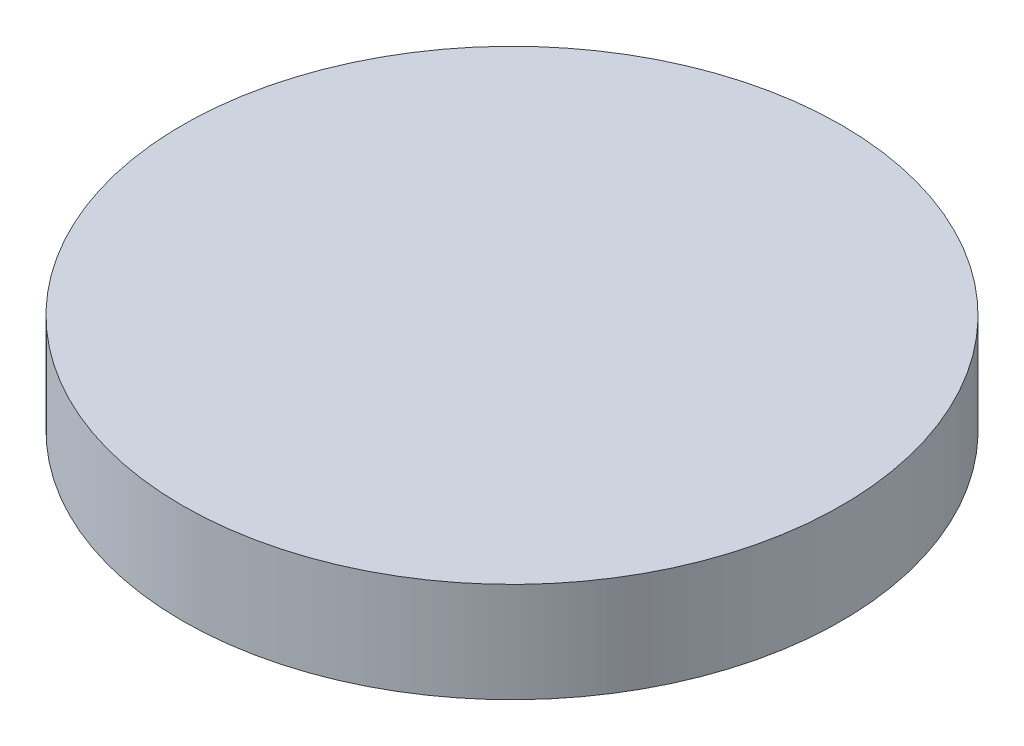
SolidWorks part; units mm, degrees
ref_plane "Front" through (0, 0, 0) normal (0, 0, 1) x (1, 0, 0)
ref_plane "Top" through (0, 0, 0) normal (0, 1, 0) x (1, 0, 0)
ref_plane "Right" through (0, 0, 0) normal (1, 0, 0) x (0, 0, -1)
sketch "Base Sketch" plane through (0, 0, 0) normal (0, 1, 0) x (1, 0, 0)
  circle A0 centre (0, 0) radius 1.65
  dimension "D1" = 3.3
extrude "Base" add sketch "Base Sketch" along normal blind 0.5
sketch "Base Slot Sketch" [suppressed] plane through (0, 1, 0) normal (0, 1, 0) x (-1, 0, 0)
  line L0 (-1.6008, -0.4) -> (1.6008, -0.4)
  line L1 (1.6008, 0.4) -> (-1.6008, 0.4)
  line L2 (0, 0) -> (-1.098, 0) construction
  circle A0 centre (0, 0) radius 1.65 construction
  arc A1 (1.6008, -0.4) -> (1.6008, 0.4) centre (0, 0) ccw
  arc A2 (-1.6008, 0.4) -> (-1.6008, -0.4) centre (0, 0) ccw
  dimension "D1" = 0.8
extrude "Base Slot" [suppressed] cut sketch "Base Slot Sketch" against normal blind 0.2
sketch "PLLT Extrusion Sketch" [suppressed] plane through (0, 2.5, 0) normal (0, 1, 0) x (-1, 0, 0)
  circle A0 centre (0, 0) radius 2.25
  dimension "D1" = 4.5
extrude "PLLT Extrusion" [suppressed] add sketch "PLLT Extrusion Sketch" along normal blind 7.5
sketch "PLLT Slot Sketch" [suppressed] plane through (0, 10, 0) normal (0, 1, 0) x (-1, 0, 0)
  line L0 (0, 0) -> (0, -3.3239) construction
  line L3 (0.4, -2.2142) -> (0.4, 2.2142)
  line L4 (-0.4, -2.2142) -> (-0.4, 2.2142)
  circle A0 centre (0, 0) radius 2.25 construction
  arc A1 (0.4, 2.2142) -> (-0.4, 2.2142) centre (0, 0) ccw
  arc A2 (-0.4, -2.2142) -> (0.4, -2.2142) centre (0, 0) ccw
  dimension "D1" = 0.8
extrude "PLLT Slot" [suppressed] cut sketch "PLLT Slot Sketch" against normal blind 0.2
sketch "PLL Handle Sketch" [suppressed] plane through (0, 2.8, 0) normal (0, 1, 0) x (-1, 0, 0)
  line L0 (-2.4928, 0.7389) -> (-1.1985, 5.1053)
  line L1 (2.4928, 0.7389) -> (1.1985, 5.1053)
  arc A0 (-2.4928, 0.7389) -> (2.4928, 0.7389) centre (0, 0) ccw
  arc A1 (1.1985, 5.1053) -> (-1.1985, 5.1053) centre (0, 4.75) ccw
  dimension "Large Dia" = 5.2
  dimension "Small Dia" = 2.5
  dimension "C to C" = 8.6
extrude "PLL Handle" [suppressed] add sketch "PLL Handle Sketch" along normal blind 1.8
sketch "PLL Handle Boss Sketch" [suppressed] plane through (0, 4.6, 0) normal (0, 1, 0) x (-1, 0, 0)
  line L0 (0, 0) -> (0, 10.6143) construction
  line L1 (0.5, -2.5515) -> (0.5, 4.4)
  line L2 (-0.5, -2.5515) -> (-0.5, 4.4)
  line L3 (0.5, 4.4) -> (-0.5, 4.4)
  arc A0 (-2.4928, 0.7389) -> (2.4928, 0.7389) centre (0, 0) ccw construction
  arc A1 (-0.5, -2.5515) -> (0.5, -2.5515) centre (0, 0) ccw
  dimension "Width" = 1
  dimension "Length" = 7
extrude "PLL Handle Boss" [suppressed] add sketch "PLL Handle Boss Sketch" along normal blind 0.3
